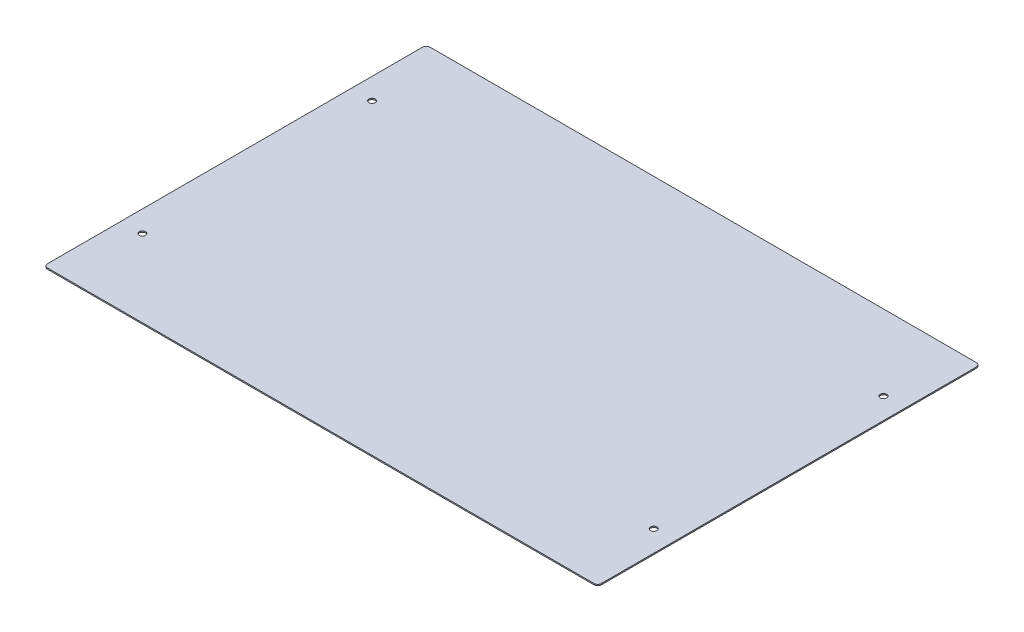
SolidWorks part; units mm, degrees
material "Polysterene"
ref_plane "Front Plane" through (0, 0, 0) normal (0, 0, 1) x (1, 0, 0)
ref_plane "Top Plane" through (0, 0, 0) normal (0, 1, 0) x (1, 0, 0)
ref_plane "Right Plane" through (0, 0, 0) normal (1, 0, 0) x (0, 0, -1)
sketch "Sketch1" plane through (0, 0, 0) normal (0, 1, 0) x (1, 0, 0)
  line L0 (0, 155.9) -> (0, -155.9) construction
  line L5 (-225.75, -155.9) -> (225.75, 155.9) construction
  line L6 (-225.75, 155.9) -> (225.75, -155.9) construction
  line L7 (-225.75, 136.85) -> (225.75, 136.85) construction
  line L8 (-225.75, 0) -> (225.75, 0) construction
  line L9 (-225.75, 146.375) -> (225.75, 146.375) construction
  line L10 (-203.525, 155.9) -> (-203.525, 133.675) construction
  line L11 (-206.7, 155.9) -> (-206.7, -155.9) construction
  line L12 (-216.225, 155.9) -> (-216.225, -155.9) construction
  line L13 (-225.75, -136.85) -> (225.75, -136.85) construction
  line L14 (-139.7, 146.375) -> (139.7, 146.375) construction
  line L15 (-203.525, 133.675) -> (-225.75, 133.675) construction
  line L16 (-203.525, 155.9) -> (203.525, 155.9)
  line L17 (-206.7, 155.9) -> (-225.75, 155.9) construction
  line L18 (-225.75, -133.675) -> (-203.525, -133.675) construction
  line L19 (-203.525, -133.675) -> (-203.525, -155.9) construction
  line L20 (203.525, 155.9) -> (203.525, 133.675) construction
  line L21 (203.525, 133.675) -> (225.75, 133.675) construction
  line L22 (203.525, -155.9) -> (203.525, -133.675) construction
  line L23 (203.525, -133.675) -> (225.75, -133.675) construction
  line L24 (-203.525, -155.9) -> (203.525, -155.9)
  line L25 (-225.75, -133.675) -> (-225.75, 133.675)
  line L26 (225.75, -133.675) -> (225.75, 133.675)
  line L27 (-225.75, 155.9) -> (-225.75, 136.85) construction
  line L28 (-225.75, 133.675) -> (-225.75, 152.9)
  line L29 (-222.75, 155.9) -> (-203.525, 155.9)
  line L30 (-203.525, -155.9) -> (-222.75, -155.9)
  line L31 (-225.75, -152.9) -> (-225.75, -133.675)
  line L32 (225.75, -133.675) -> (225.75, -152.9)
  line L33 (222.75, -155.9) -> (203.525, -155.9)
  line L34 (225.75, 133.675) -> (225.75, 152.9)
  line L35 (222.75, 155.9) -> (203.525, 155.9)
  arc A0 (-225.75, 152.9) -> (-222.75, 155.9) centre (-222.75, 152.9) cw
  arc A1 (-222.75, -155.9) -> (-225.75, -152.9) centre (-222.75, -152.9) cw
  arc A2 (225.75, -152.9) -> (222.75, -155.9) centre (222.75, -152.9) cw
  arc A3 (225.75, 152.9) -> (222.75, 155.9) centre (222.75, 152.9) ccw
  point P0 (0, 0)
  point P28 (0, 146.375)
  dimension "D5" = 3
  dimension "D1" = 311.8
  dimension "D2" = 451.5
  dimension "D3" = 19.05
  dimension "D4" = 9.525
  dimension "D6" = 279.4
  dimension "D9" = 19.05
  dimension "D10" = 9.525
  dimension "D13" = 3.175
  dimension "D14" = 3.175
extrude "Boss-Extrude1" add sketch "Sketch1" along normal blind 1
sketch "Sketch5" plane through (0, 1, 0) normal (0, 1, 0) x (1, 0, 0)
  line L0 (0, 218.0287) -> (0, -238.3378) construction
  line L1 (-329.8001, 0) -> (285.342, 0) construction
  circle A6 centre (208.4499, -92.899) radius 4 construction
  circle A8 centre (-208.4499, 94.399) radius 4 construction
  circle A9 centre (-208.4499, 94.399) radius 4 construction
  circle A10 centre (-208.4499, 94.399) radius 2.6
  circle A13 centre (208.4499, 94.399) radius 2.6
  circle A15 centre (-208.4499, -92.899) radius 4 construction
  circle A16 centre (-208.4499, -92.899) radius 2.6
  circle A17 centre (208.4499, -92.899) radius 2.6
  dimension "D1" = 5.2
  dimension "D2" = 5.2
  dimension "D3" = 5.2
  dimension "D4" = 94.399
  dimension "D5" = 92.899
  dimension "D6" = 208.4499
  dimension "D7" = 208.4499
  dimension "D8" = 92.899
extrude "Cut-Extrude1" cut sketch "Sketch5" against normal through all
